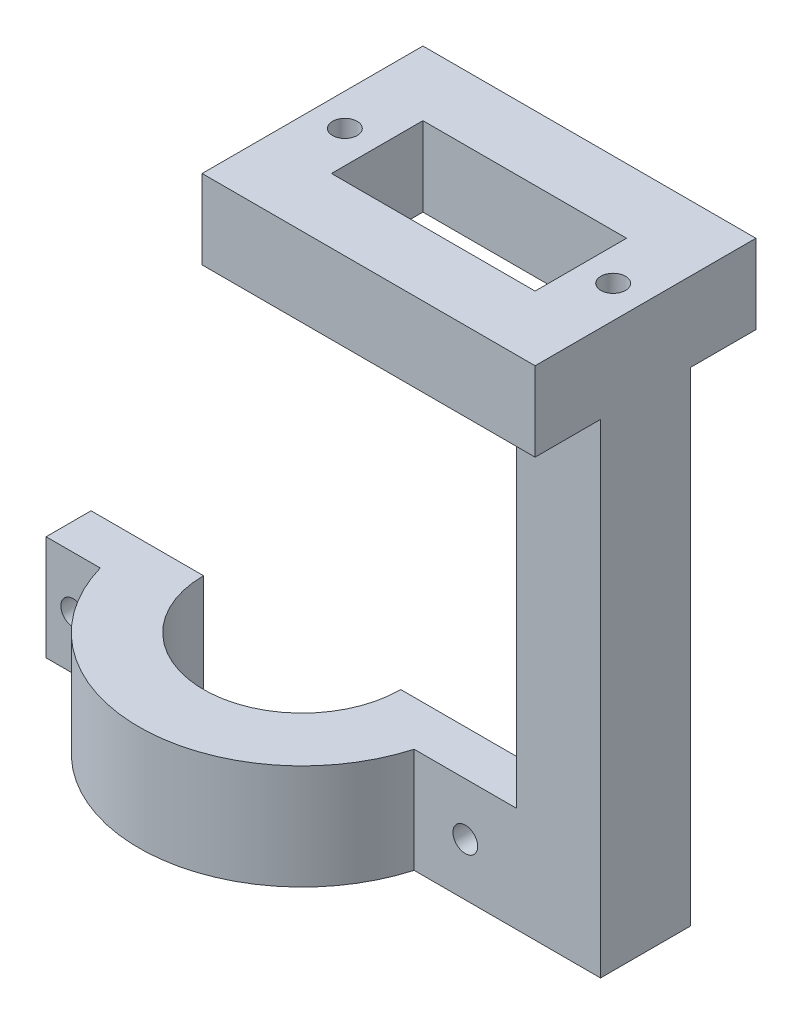
SolidWorks part; units mm, degrees
ref_plane "前基準面" through (0, 0, 0) normal (0, 0, 1) x (1, 0, 0)
ref_plane "上基準面" through (0, 0, 0) normal (0, 1, 0) x (1, 0, 0)
ref_plane "右基準面" through (0, 0, 0) normal (1, 0, 0) x (0, 0, -1)
sketch "草圖1" plane through (0, 0, 0) normal (0, 1, 0) x (1, 0, 0)
  line L1 (-15.75, 7.075) -> (15.75, 7.075)
  line L2 (-15.75, 7.075) -> (-15.75, -7.075)
  line L3 (-15.75, -7.075) -> (15.75, -7.075)
  line L4 (15.75, 7.075) -> (15.75, -7.075)
  line L5 (-15.75, 7.075) -> (15.75, -7.075) construction
  line L6 (-15.75, -7.075) -> (15.75, 7.075) construction
  point P0 (0, 0)
  dimension "D1" = 14.15
  dimension "D2" = 31.5
extrude "伸長-薄件1" add sketch "草圖1" along normal blind 12.25 thin thin type one direction wall 10
sketch "草圖2" plane through (0, 12.25, 0) normal (0, 1, 0) x (1, 0, 0)
  line L0 (-1014.255, 0) -> (48985.745, 0) construction
  line L1 (-15.75, 7.075) -> (-15.75, -7.075) construction
  line L2 (-20.75, -988.4004) -> (-20.75, 49011.5996) construction
  line L3 (-25.75, 17.075) -> (-20.75, 17.075) construction
  line L4 (-25.75, 17.075) -> (-25.75, 11.5996) construction
  line L5 (-25.75, 11.5996) -> (-20.75, 11.5996) construction
  line L6 (-20.75, 17.075) -> (-20.75, 11.5996) construction
  line L7 (25.75, 17.075) -> (20.75, 17.075) construction
  line L8 (25.75, 17.075) -> (25.75, 12.4477) construction
  line L9 (25.75, 12.4477) -> (20.75, 12.4477) construction
  line L10 (20.75, 17.075) -> (20.75, 12.4477) construction
  line L11 (20.75, -987.5523) -> (20.75, 49012.4477) construction
  circle A0 centre (-20.75, 0) radius 1.91
  circle A1 centre (20.75, 0) radius 1.91
  point P5 (-15.75, 0)
  dimension "D3" = 3.82
  dimension "D4" = 3.82
  dimension "D1" = 5
  dimension "D2" = 5
extrude "除料-伸長1" cut sketch "草圖2" against normal through all
sketch "草圖4" plane through (0, 0, 0) normal (0, -1, 0) x (1, 0, 0)
  line L0 (-1000, 0) -> (49000, 0) construction
  line L1 (25.75, 17.075) -> (25.75, -17.075) construction
  line L2 (12.75, 6.955) -> (25.75, 6.955)
  line L3 (12.75, 6.955) -> (12.75, -6.955)
  line L4 (12.75, -6.955) -> (25.75, -6.955)
  line L5 (25.75, 6.955) -> (25.75, -6.955)
  line L6 (12.75, 6.955) -> (25.75, -6.955) construction
  line L7 (12.75, -6.955) -> (25.75, 6.955) construction
  point P1 (19.25, 0)
  dimension "D1" = 13.91
  dimension "D2" = 13
extrude "填料-伸長1" add sketch "草圖4" along normal blind 74.82
sketch "草圖5" plane through (12.75, 0, 0) normal (-1, 0, 0) x (0, 0, 1)
  line L0 (6.955, -74.82) -> (6.955, 0) construction
  line L1 (-6.955, -74.82) -> (6.955, -74.82)
  line L2 (-6.955, -74.82) -> (-6.955, -58.59)
  line L3 (-6.955, -58.59) -> (6.955, -58.59)
  line L4 (6.955, -74.82) -> (6.955, -58.59)
  dimension "D1" = 16.23
extrude "填料-伸長2" add sketch "草圖5" along normal blind 16
sketch "草圖7" plane through (3.6267, -74.82, 0) normal (0, -1, 0) x (1, 0, 0)
  circle A0 centre (-30.9782, 0) radius 15.25
  dimension "D1" = 30.5
extrude "伸長-薄件2" add sketch "草圖7" against normal blind 16.23 thin
ref_plane "平面1" through (-60, 0, 0) normal (1, 0, 0) x (0, 0, -1)
ref_plane "平面2" through (-55, 0, 0) normal (1, 0, 0) x (0, 0, -1)
ref_plane "平面3" through (-60, 0, 0) normal (1, 0, 0) x (0, 0, -1)
sketch "草圖15" plane through (0, 0, -6.955) normal (0, 0, -1) x (-1, 0, 0)
  line L0 (-996.9218, -66.705) -> (49003.0782, -66.705) construction
  line L1 (3.0782, -74.82) -> (3.0782, -58.59) construction
  line L2 (-4.8359, -1058.59) -> (-4.8359, 48941.41) construction
  line L3 (3.0782, -58.59) -> (-12.75, -58.59) construction
  circle A0 centre (-4.8359, -66.705) radius 1.91
  point P5 (3.0782, -66.705)
  point P10 (-4.8359, -58.59)
  dimension "D1" = 3.82
extrude "除料-伸長6" cut sketch "草圖15" against normal through all
ref_plane "平面4" through (-60, 0, 0) normal (1, 0, 0) x (0, 0, -1)
sketch "草圖16" plane through (-60, 0, 0) normal (1, 0, 0) x (0, 0, -1)
  line L1 (6.955, -58.59) -> (-6.955, -58.59)
  line L2 (6.955, -58.59) -> (6.955, -74.82)
  line L3 (6.955, -74.82) -> (-6.955, -74.82)
  line L4 (-6.955, -58.59) -> (-6.955, -74.82)
extrude "填料-伸長4" add sketch "草圖16" along normal blind 10
sketch "草圖17" plane through (0, 0, -6.955) normal (0, 0, -1) x (-1, 0, 0)
  line L0 (-948.3753, -66.705) -> (49051.6247, -66.705) construction
  line L1 (51.6247, -74.82) -> (51.6247, -58.59) construction
  line L2 (55.8124, -1058.59) -> (55.8124, 48941.41) construction
  line L3 (51.6247, -58.59) -> (60, -58.59) construction
  circle A0 centre (55.8124, -66.705) radius 1.91
  point P5 (51.6247, -66.705)
  point P10 (55.8124, -58.59)
  dimension "D1" = 3.82
extrude "除料-伸長7" cut sketch "草圖17" against normal through all
sketch "草圖23" plane through (0, -58.59, 0) normal (0, 1, 0) x (1, 0, 0)
  line L0 (12.75, -6.955) -> (12.75, 6.955) construction
  line L1 (12.75, 0) -> (-76.5807, 0)
  line L2 (12.75, 0) -> (12.75, 36.1048)
  line L3 (12.75, 36.1048) -> (-76.5807, 36.1048)
  line L4 (-76.5807, 0) -> (-76.5807, 36.1048)
extrude "除料-伸長12" cut sketch "草圖23" against normal blind 57
